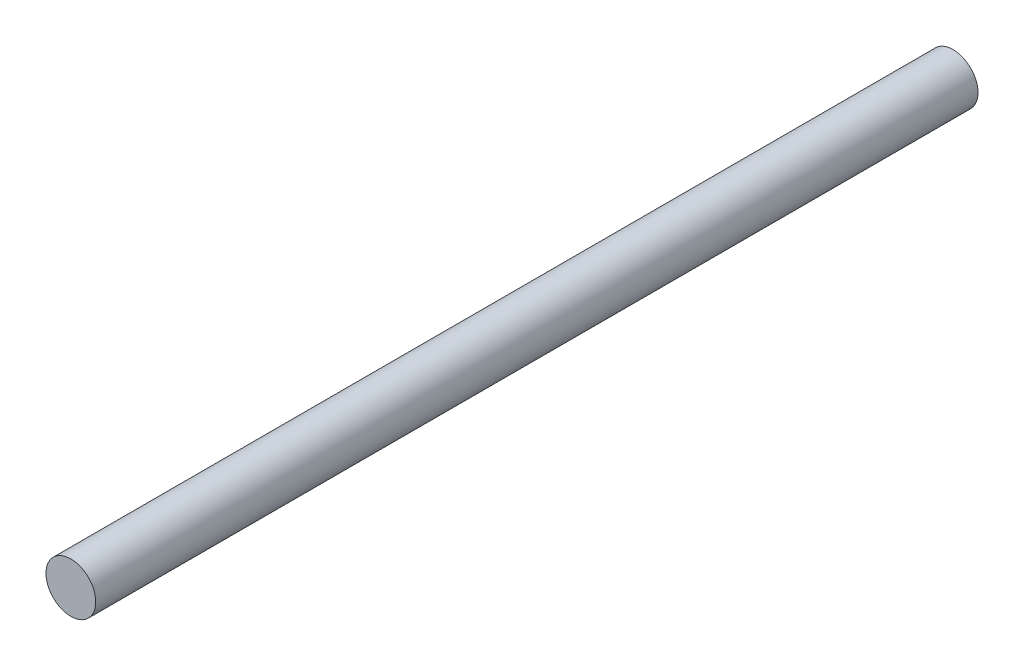
SolidWorks part; units mm, degrees
ref_plane "Front Plane" through (0, 0, 0) normal (0, 0, 1) x (1, 0, 0)
ref_plane "Top Plane" through (0, 0, 0) normal (0, 1, 0) x (1, 0, 0)
ref_plane "Right Plane" through (0, 0, 0) normal (1, 0, 0) x (0, 0, -1)
sketch "Sketch2" plane through (0, 0, 0) normal (0, 0, 1) x (1, 0, 0)
  circle A0 centre (0, 0) radius 6.35
  dimension "D1" = 12.7
extrude "Boss-Extrude1" add sketch "Sketch2" along normal blind 225
